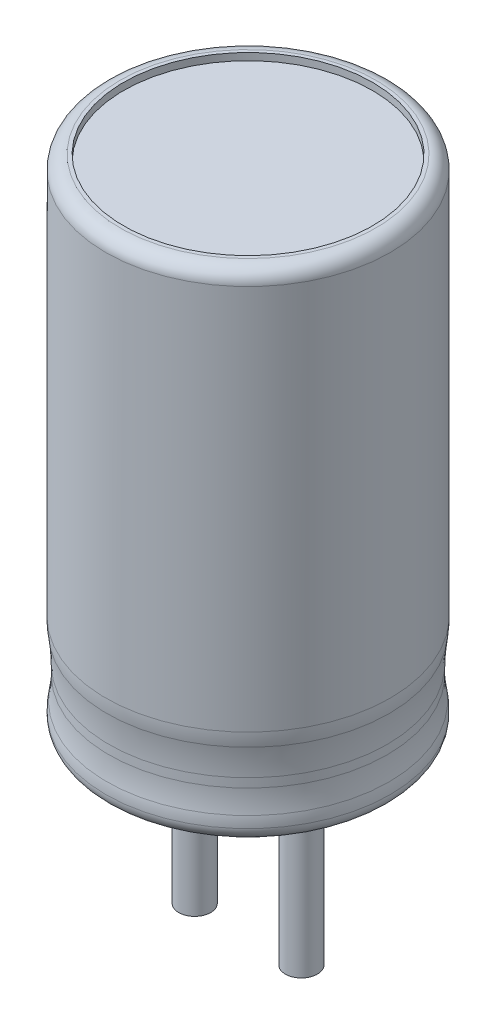
SolidWorks part; units mm, degrees
ref_plane "Front Plane" through (0, 0, 0) normal (0, 0, 1) x (1, 0, 0)
ref_plane "Top Plane" through (0, 0, 0) normal (0, 1, 0) x (1, 0, 0)
ref_plane "Right Plane" through (0, 0, 0) normal (1, 0, 0) x (0, 0, -1)
sketch "Sketch1" plane through (0, 0, 0) normal (0, 0, 1) x (1, 0, 0)
  line L0 (2, 7) -> (0, 7)
  line L1 (0, 7) -> (0, 0)
  line L2 (0, 0) -> (1.9701, 0)
  line L3 (1.9567, 0.6618) -> (1.9567, 0.7881)
  line L4 (2, 1.3737) -> (2, 7)
  line L5 (0, 7) -> (0, 0) construction
  arc A0 (1.9701, 0) -> (1.9856, 0.3477) centre (1.2282, 0.2072) ccw
  arc A1 (1.9856, 0.3477) -> (1.9567, 0.6618) centre (3.6795, 0.6618) cw
  arc A2 (1.9567, 0.7881) -> (1.9856, 1.1788) centre (4.6142, 0.7881) cw
  arc A3 (1.9856, 1.1788) -> (2, 1.3737) centre (0.6744, 1.3737) ccw
  point P14 (0, 0)
  point P15 (0, 0)
  point P16 (4.8262, 0)
  point P17 (0, 0)
  point P18 (1.6537, 0.0745)
  point P19 (0, 0)
  point P20 (2.1777, 1.3309)
  point P21 (-0.0329, 1.1795)
  point P22 (1.9117, 1.8222)
  point P23 (1.7089, 0.2035)
  point P24 (1.9701, 1.1508)
  point P25 (2.0628, 0.8198)
  point P26 (2.1107, 0.6929)
  point P27 (1.9701, 0)
  point P28 (2, 0.6737)
  point P29 (0, 0)
  point P30 (0, 0)
  point P31 (2.0449, 0.3037)
  point P32 (1.9701, 0.6026)
  point P33 (1.9646, 0.857)
  point P34 (1.9646, 1.022)
  point P35 (1.9864, 1.3879)
  point P36 (0, 0)
  point P37 (1.9866, 1.3856)
  point P38 (1.9876, 1.3737)
  point P39 (0, 0)
  point P40 (1.9567, 0.7881)
  point P41 (0, 0)
  point P42 (0, 0)
  point P43 (1.9856, 0.3477)
  dimension "D1" = 7
  dimension "D2" = 2
revolve "Revolve1" add sketch "Sketch1" angle 360 about L5
sketch "Sketch2" plane through (0, 7, 0) normal (0, 1, 0) x (-1, 0, 0)
  circle A0 centre (0, 0) radius 1.75
  dimension "D1" = 3.5
extrude "Cut-Extrude1" cut sketch "Sketch2" against normal blind 0.1
ref_plane "Plane1" through (0, 0, 0) normal (0, 0, -1) x (-1, 0, 0)
sketch "Sketch4" plane through (0, 0, 0) normal (0, 0, -1) x (-1, 0, 0)
  line L0 (-0.975, -2.5) -> (-0.75, -2.5)
  line L1 (-0.75, -2.5) -> (-0.75, 0)
  line L2 (-0.75, 0) -> (-0.975, 0)
  line L3 (-0.975, 0) -> (-0.975, -2.5)
  line L4 (-0.75, -2.5) -> (-0.75, 0) construction
  dimension "D1" = 0.75
  dimension "D2" = 0.225
revolve "Revolve2" add sketch "Sketch4" angle 360 about L4
fillet "Fillet1" radius 0.2 2 edges at (2, 7, 0) (1.9701, 0, 0)
mirror "Simetría3" about plane through (0, 0, 0) normal (1, 0, 0) of "Revolve2"
